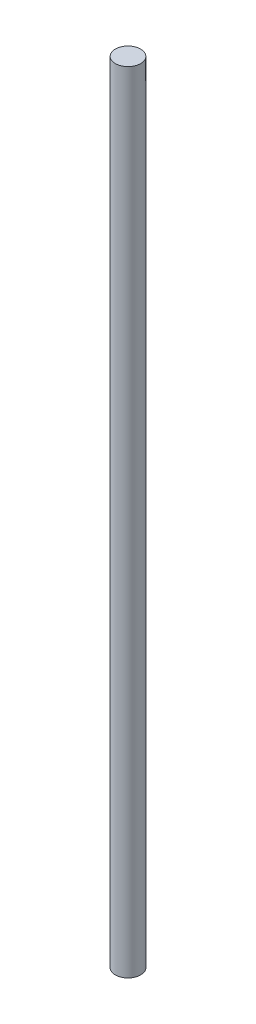
SolidWorks part; units mm, degrees
ref_plane "Plan de face" through (0, 0, 0) normal (0, 0, 1) x (1, 0, 0)
ref_plane "Plan de dessus" through (0, 0, 0) normal (0, 1, 0) x (1, 0, 0)
ref_plane "Plan de droite" through (0, 0, 0) normal (1, 0, 0) x (0, 0, -1)
sketch "Esquisse1" plane through (0, 0, 0) normal (0, 0, 1) x (1, 0, 0)
  line L0 (0, 256.2059) -> (0, -243.7941)
  dimension "D1" = 500
revolve "Révol.-Mince2" add sketch "Esquisse1" angle 360 about L0 wall 8
